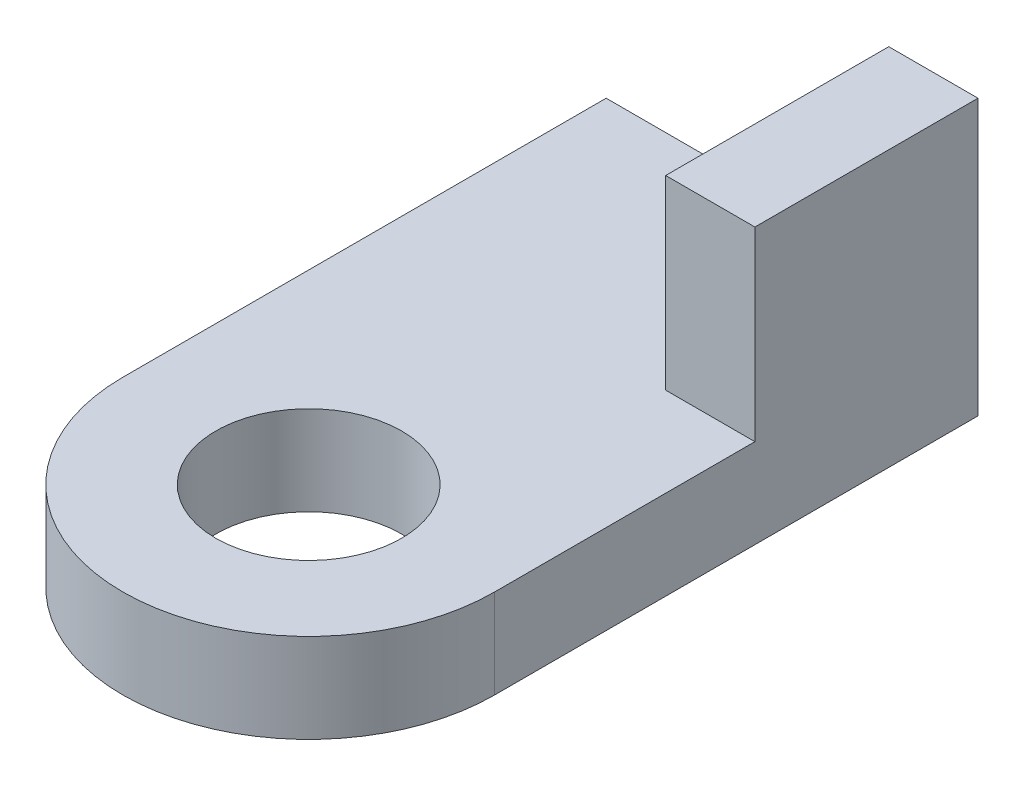
SolidWorks part; units mm, degrees
ref_plane "Front Plane" through (0, 0, 0) normal (0, 0, 1) x (1, 0, 0)
ref_plane "Top Plane" through (0, 0, 0) normal (0, 1, 0) x (1, 0, 0)
ref_plane "Right Plane" through (0, 0, 0) normal (1, 0, 0) x (0, 0, -1)
sketch "Sketch2" plane through (0, 0, 0) normal (0, 1, 0) x (1, 0, 0)
  line L0 (0, 0) -> (50, 0)
  line L1 (50, 0) -> (50, -65)
  line L2 (50, -65) -> (0, -65)
  line L3 (0, -65) -> (0, 0)
  dimension "D1" = 65
  dimension "D2" = 50
extrude "Boss-Extrude1" add sketch "Sketch2" along normal blind 12 contours L3 L0 L1 L2
sketch "Sketch3" plane through (0, 12, 0) normal (0, 1, 0) x (1, 0, 0)
  line L0 (50, -65) -> (0, -65) construction
  line L1 (0, -65) -> (50, -65)
  arc A0 (0, -65) -> (50, -65) centre (25, -65) ccw
  dimension "D1" = 50
extrude "Boss-Extrude2" add sketch "Sketch3" against normal blind 12 contours L1 A0
sketch "Sketch5" plane through (0, 12, 0) normal (0, 1, 0) x (1, 0, 0)
  circle A0 centre (25, -65) radius 12.5
  dimension "D1" = 25
extrude "Cut-Extrude1" cut sketch "Sketch5" against normal blind 12
sketch "Sketch7" plane through (0, 12, 0) normal (0, 1, 0) x (1, 0, 0)
  line L0 (50, 0) -> (38, 0)
  line L1 (50, 0) -> (50, -65) construction
  line L2 (0, 0) -> (50, 0) construction
  line L3 (38, 0) -> (38, -30)
  line L4 (38, -30) -> (50, -30)
  line L5 (50, -30) -> (50, 0)
  dimension "D1" = 30
  dimension "D2" = 12
extrude "Boss-Extrude3" add sketch "Sketch7" along normal blind 25 contours L5 L0 L3 L4
